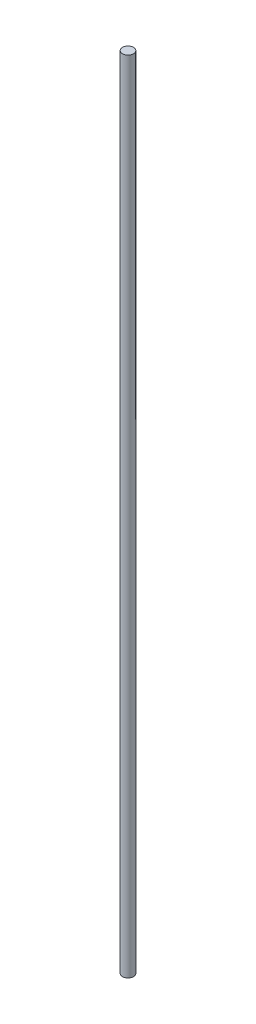
SolidWorks part; units mm, degrees
material "Alliage 1060"
ref_plane "Plan de face" through (0, 0, 0) normal (0, 0, 1) x (1, 0, 0)
ref_plane "Plan de dessus" through (0, 0, 0) normal (0, 1, 0) x (1, 0, 0)
ref_plane "Plan de droite" through (0, 0, 0) normal (1, 0, 0) x (0, 0, -1)
sketch "Esquisse1" plane through (0, 0, 0) normal (0, 1, 0) x (1, 0, 0)
  circle A0 centre (0, 0) radius 5
  dimension "D1" = 5
extrude "Boss.-Extru.1" add sketch "Esquisse1" along normal blind 720
equation "\"r2\"=5"
equation "\"r1\"=30.9"
equation "\"h1\"=30"
equation "\"h2\"=720"
equation "\"D1@Esquisse1\"=\"r2\""
equation "\"D1@Boss.-Extru.1\"=\"h2\""
